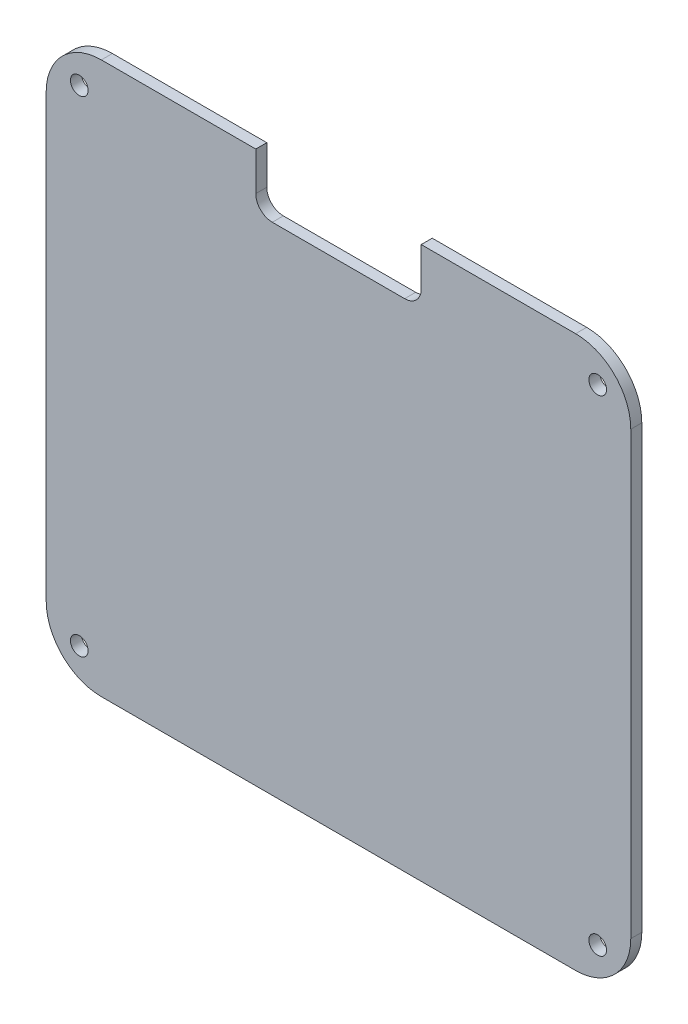
SolidWorks part; units mm, degrees
ref_plane "Front Plane" through (0, 0, 0) normal (0, 0, 1) x (1, 0, 0)
ref_plane "Top Plane" through (0, 0, 0) normal (0, 1, 0) x (1, 0, 0)
ref_plane "Right Plane" through (0, 0, 0) normal (1, 0, 0) x (0, 0, -1)
sketch "Sketch1" plane through (0, 0, 0) normal (0, 0, 1) x (1, 0, 0)
  line L4 (-43, 260) -> (43, 260)
  line L5 (53, 270) -> (53, 350)
  line L6 (43, 360) -> (-43, 360)
  line L7 (-53, 350) -> (-53, 270)
  arc A4 (43, 260) -> (53, 270) centre (43, 270) ccw
  arc A5 (53, 350) -> (43, 360) centre (43, 350) ccw
  arc A6 (-43, 360) -> (-53, 350) centre (-43, 350) ccw
  arc A7 (-53, 270) -> (-43, 260) centre (-43, 270) ccw
extrude "Boss-Extrude1" add sketch "Sketch1" against normal blind 2
sketch "Sketch2" plane through (0, 0, 0) normal (0, 0, 1) x (1, 0, 0)
  line L0 (43, 360) -> (-43, 360) construction
  line L1 (-15, 360) -> (15, 360)
  line L2 (-15, 360) -> (-15, 350)
  line L3 (-15, 350) -> (15, 350)
  line L4 (15, 360) -> (15, 350)
  line L5 (0, 252) -> (0, 388.9824) construction
  dimension "D1" = 15
  dimension "D2" = 30
  dimension "D3" = 10
extrude "Cut-Extrude1" cut sketch "Sketch2" against normal through all
fillet "Fillet1" radius 3 2 edges at (-15, 350, -1) (15, 350, -1)
sketch "Sketch3" plane through (0, 0, 0) normal (0, 0, 1) x (1, 0, 0)
  line L0 (53, 270) -> (53, 350) construction
  line L1 (43, 360) -> (15, 360) construction
  line L2 (-43, 260) -> (43, 260) construction
  line L3 (0, 350) -> (0, 288.1349) construction
  line L4 (-12, 350) -> (12, 350) construction
  circle A0 centre (47, 354) radius 1.6
  circle A1 centre (47, 266) radius 1.6
  circle A2 centre (-47, 266) radius 1.6
  circle A3 centre (-47, 354) radius 1.6
  dimension "D1" = 6
  dimension "D2" = 6
  dimension "D3" = 6
  dimension "D4" = 6
extrude "Cut-Extrude2" cut sketch "Sketch3" against normal through all
